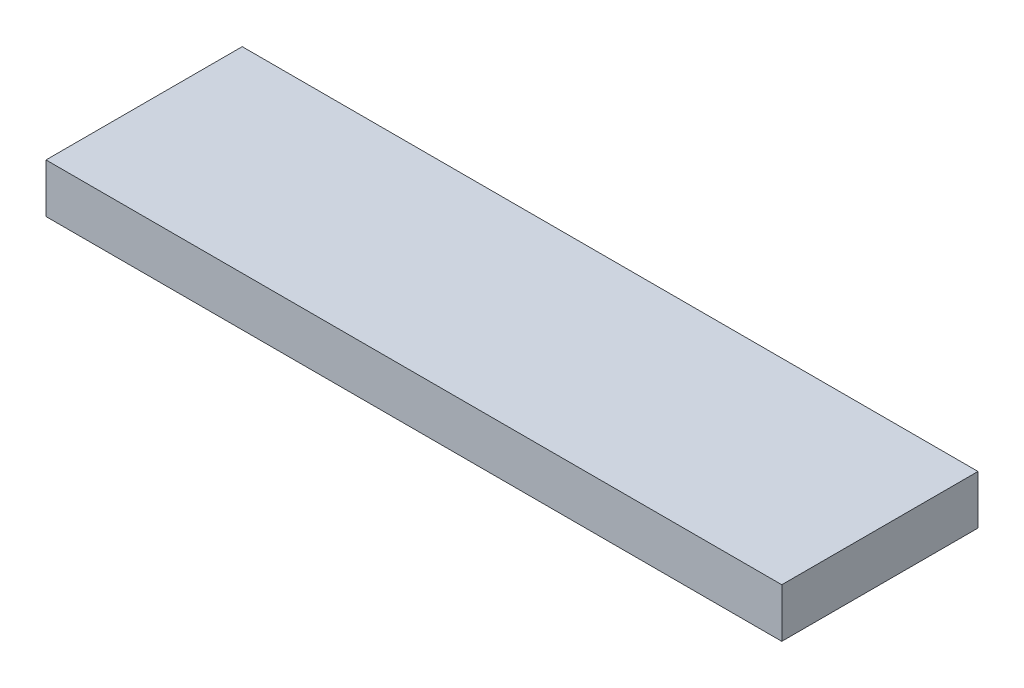
SolidWorks part; units mm, degrees
ref_plane "Front Plane" through (0, 0, 0) normal (0, 0, 1) x (1, 0, 0)
ref_plane "Top Plane" through (0, 0, 0) normal (0, 1, 0) x (1, 0, 0)
ref_plane "Right Plane" through (0, 0, 0) normal (1, 0, 0) x (0, 0, -1)
sketch "Sketch1" plane through (0, 0, 0) normal (0, 1, 0) x (1, 0, 0)
  line L1 (0, 0) -> (15, 0)
  line L2 (0, 0) -> (0, -4)
  line L3 (0, -4) -> (15, -4)
  line L4 (15, 0) -> (15, -4)
  dimension "D1" = 15
  dimension "D2" = 4
extrude "Boss-Extrude1" add sketch "Sketch1" along normal blind 1
